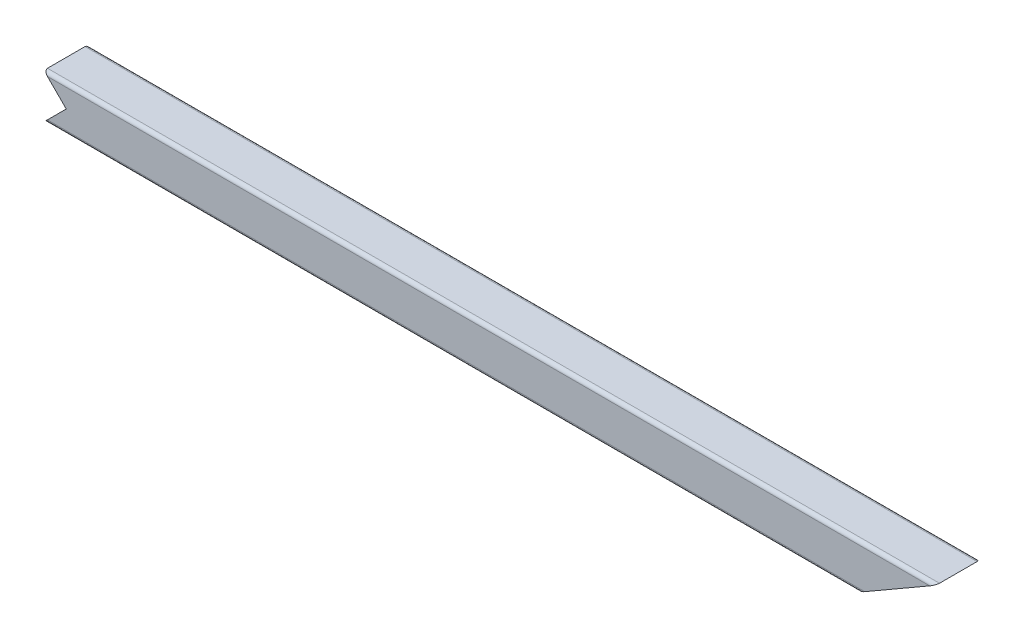
SolidWorks part; units mm, degrees
material "Plain Carbon Steel"
ref_plane "Front Plane" through (0, 0, 0) normal (0, 0, 1) x (1, 0, 0)
ref_plane "Top Plane" through (0, 0, 0) normal (0, 1, 0) x (1, 0, 0)
ref_plane "Right Plane" through (0, 0, 0) normal (1, 0, 0) x (0, 0, -1)
sketch "Sketch1" plane through (0, 0, 0) normal (1, 0, 0) x (0, 0, -1)
  line L0 (0, 2.54) -> (0, 29.21)
  line L1 (-2.54, 31.75) -> (-29.21, 31.75)
  line L2 (-31.75, 29.21) -> (-31.75, 2.54)
  line L3 (-29.21, 0) -> (-2.54, 0)
  line L4 (-4.1275, 4.1275) -> (-4.1275, 27.6225)
  line L5 (-4.1275, 27.6225) -> (-27.6225, 27.6225)
  line L6 (-27.6225, 27.6225) -> (-27.6225, 4.1275)
  line L7 (-27.6225, 4.1275) -> (-4.1275, 4.1275)
  arc A0 (-31.75, 2.54) -> (-29.21, 0) centre (-29.21, 2.54) ccw
  arc A1 (0, 2.54) -> (-2.54, 0) centre (-2.54, 2.54) cw
  arc A2 (0, 29.21) -> (-2.54, 31.75) centre (-2.54, 29.21) ccw
  arc A3 (-31.75, 29.21) -> (-29.21, 31.75) centre (-29.21, 29.21) cw
  arc A4 (-4.1275, 27.6225) -> (-4.1275, 27.6225) centre (-4.1275, 27.6225) ccw
  arc A5 (-27.6225, 27.6225) -> (-27.6225, 27.6225) centre (-27.6225, 27.6225) cw
  arc A6 (-27.6225, 4.1275) -> (-27.6225, 4.1275) centre (-27.6225, 4.1275) ccw
  arc A7 (-4.1275, 4.1275) -> (-4.1275, 4.1275) centre (-4.1275, 4.1275) cw
  point P12 (0, 0)
  point P15 (0, 31.75)
  point P18 (-31.75, 31.75)
  dimension "D3" = 2.54
  dimension "D1" = 31.75
  dimension "D2" = 31.75
  dimension "D4" = 4.1275
extrude "Boss-Extrude1" add sketch "Sketch1" along normal blind 508
scale "Scale1" scale about centroid uniform scaling no x scale factor 1 y scale factor 0.4 z scale factor 0.4
sketch "Sketch2" plane through (0, 0, 9.525) normal (0, 0, -1) x (-1, 0, 0)
  line L0 (-152.4, 22.225) -> (-152.4, 9.525) construction
  line L1 (-508, 22.225) -> (0, 22.225) construction
  line L2 (-508, 9.525) -> (0, 9.525) construction
  line L3 (0, 10.541) -> (0, 21.209) construction
  line L5 (-158.75, 15.875) -> (-152.4, 9.525)
  line L6 (-152.4, 22.225) -> (-132.341, 22.225)
  line L7 (-132.341, 22.225) -> (-132.341, 9.525)
  line L8 (-132.341, 9.525) -> (-152.4, 9.525)
  line L10 (-158.75, 15.875) -> (-152.4, 22.225)
  point P13 (-152.4, 15.875)
  dimension "D1" = 152.4
  dimension "D2" = 90
extrude "Cut-Extrude1" cut sketch "Sketch2" against normal up to next
sketch "Sketch3" plane through (0, 0, 9.525) normal (0, 0, -1) x (-1, 0, 0)
  line L0 (-406.0041, 22.225) -> (-384.007, 9.525)
  line L1 (-496.9371, 74.7252) -> (-276.9667, -52.2748) construction
  line L2 (-508, 22.225) -> (-152.4, 22.225) construction
  line L3 (-508, 9.525) -> (-152.4, 9.525) construction
  line L4 (-384.007, 9.525) -> (-508, 9.525)
  line L5 (-508, 9.525) -> (-508, 22.225)
  line L6 (-508, 22.225) -> (-406.0041, 22.225)
extrude "Cut-Extrude2" cut sketch "Sketch3" against normal up to next
